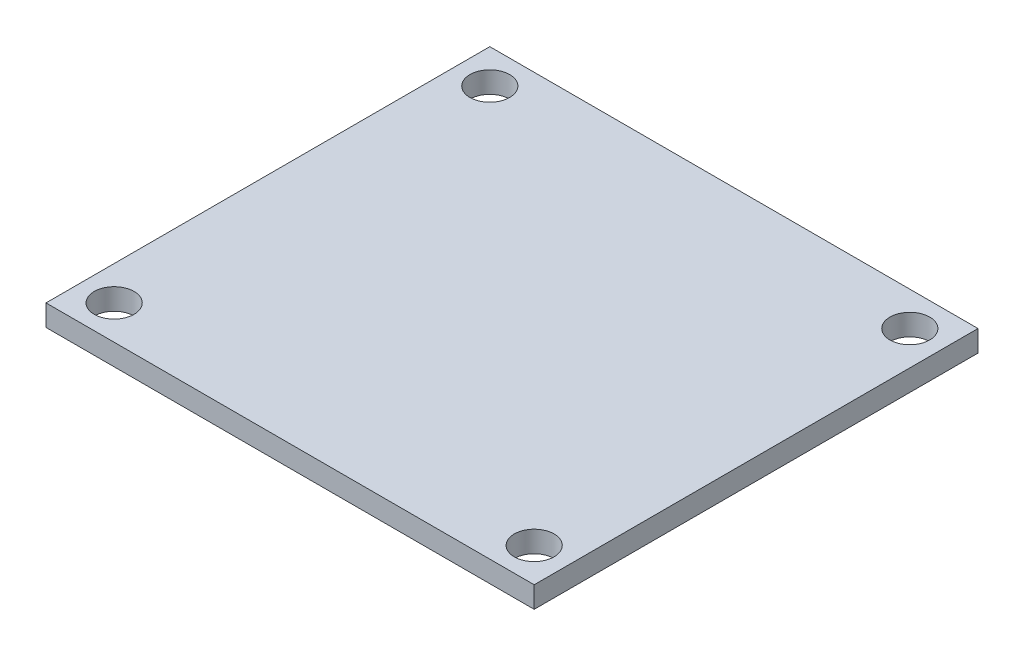
SolidWorks part; units mm, degrees
ref_plane "Front Plane" through (0, 0, 0) normal (0, 0, 1) x (1, 0, 0)
ref_plane "Top Plane" through (0, 0, 0) normal (0, 1, 0) x (1, 0, 0)
ref_plane "Right Plane" through (0, 0, 0) normal (1, 0, 0) x (0, 0, -1)
sketch "Sketch1" plane through (0, 0, 0) normal (0, 1, 0) x (1, 0, 0)
  line L1 (-19.7316, 17.8482) -> (15.1934, 17.8482)
  line L2 (-19.7316, 17.8482) -> (-19.7316, -13.9018)
  line L3 (-19.7316, -13.9018) -> (15.1934, -13.9018)
  line L4 (15.1934, 17.8482) -> (15.1934, -13.9018)
  circle A0 centre (-17.2932, 15.4098) radius 1.4224
  circle A1 centre (12.755, 15.4098) radius 1.4224
  circle A2 centre (12.755, -11.4634) radius 1.4224
  circle A3 centre (-17.2932, -11.4634) radius 1.4224
  dimension "D3" = 2.8448
  dimension "D4" = 2.8448
  dimension "D5" = 2.8448
  dimension "D6" = 2.8448
  dimension "D7" = 2.4384
  dimension "D8" = 2.4384
  dimension "D9" = 2.4384
  dimension "D10" = 2.4384
  dimension "D11" = 2.4384
  dimension "D12" = 2.4384
  dimension "D13" = 2.4384
  dimension "D14" = 2.4384
  dimension "D1" = 31.75
  dimension "D2" = 34.925
extrude "Boss-Extrude1" add sketch "Sketch1" along normal blind 1.524
